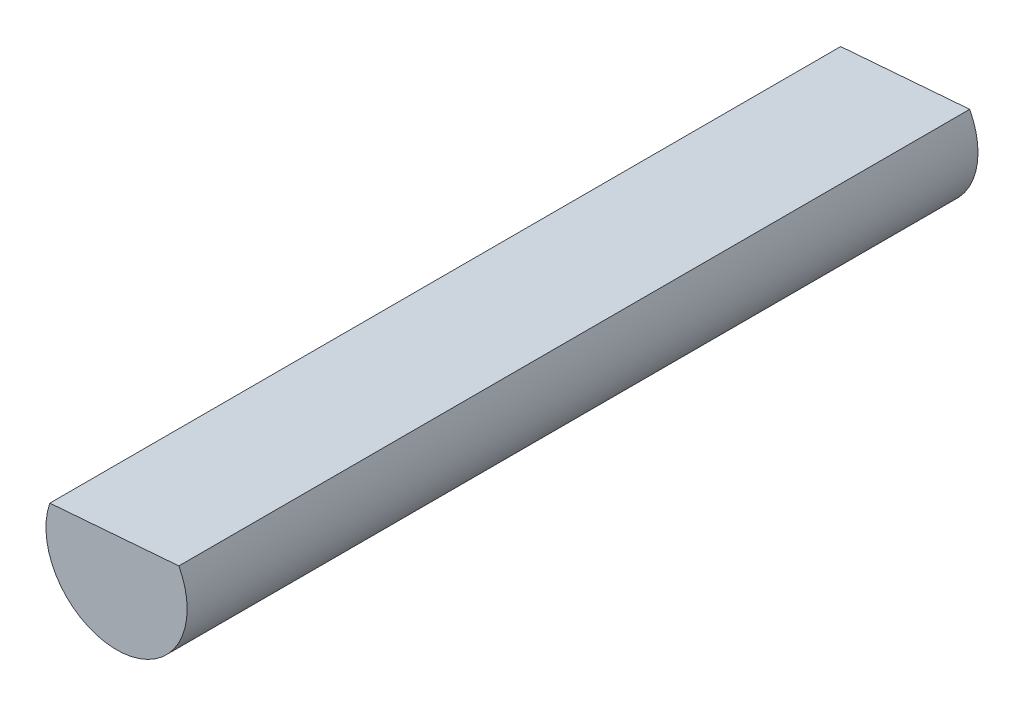
SolidWorks part; units mm, degrees
ref_plane "前视基准面" through (0, 0, 0) normal (0, 0, 1) x (1, 0, 0)
ref_plane "上视基准面" through (0, 0, 0) normal (0, 1, 0) x (1, 0, 0)
ref_plane "右视基准面" through (0, 0, 0) normal (1, 0, 0) x (0, 0, -1)
other "Configuration Table"
sketch "草图1" plane through (0, 0, 0) normal (0, 0, 1) x (1, 0, 0)
  line L0 (4.4115, 2.3534) -> (-4.7254, 1.6343)
  arc A0 (-4.7254, 1.6343) -> (4.4115, 2.3534) centre (0, 0) ccw
extrude "凸台-拉伸1" add sketch "草图1" along normal blind 56
